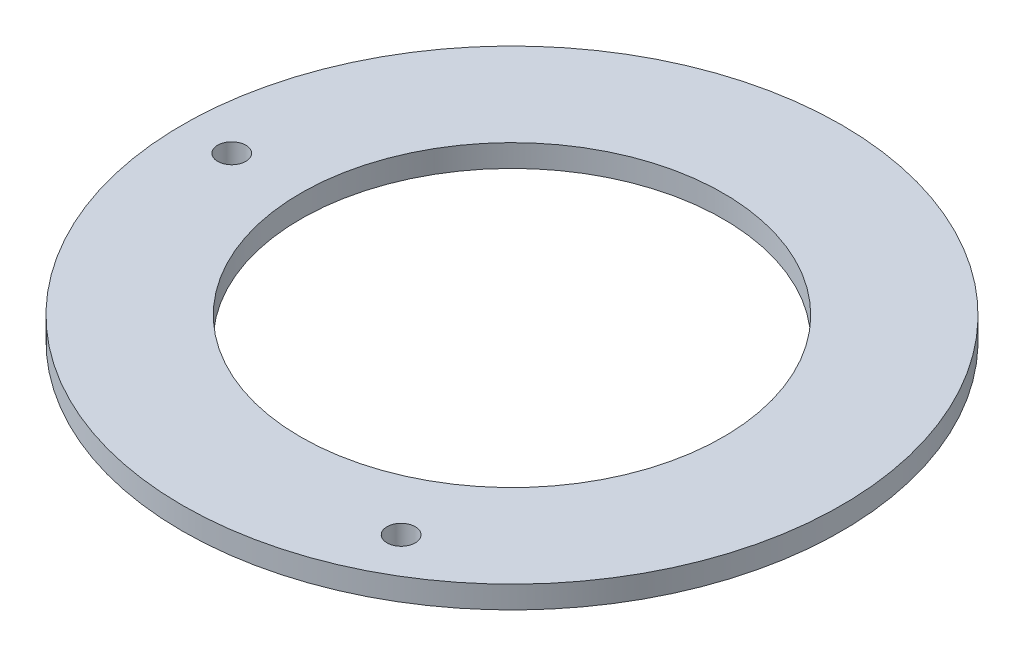
SolidWorks part; units mm, degrees
ref_plane "Front Plane" through (0, 0, 0) normal (0, 0, 1) x (1, 0, 0)
ref_plane "Top Plane" through (0, 0, 0) normal (0, 1, 0) x (1, 0, 0)
ref_plane "Right Plane" through (0, 0, 0) normal (1, 0, 0) x (0, 0, -1)
sketch "Sketch1" plane through (0, 0, 0) normal (0, 1, 0) x (1, 0, 0)
  line L0 (-39.8, 0) -> (0, 0) construction
  line L1 (-46.8, 0) -> (-39.8, 0) construction
  line L2 (0, 0) -> (22.5156, -41.0279) construction
  circle A0 centre (0, 0) radius 46.8
  circle A1 centre (0, 0) radius 30
  circle A2 centre (-39.8, 0) radius 2
  circle A3 centre (19.1479, -34.8912) radius 2
  point P6 (-46.8, 0)
  dimension "D1" = 93.6
  dimension "D2" = 60
  dimension "D4" = 4
  dimension "D5" = 4
  dimension "D3" = 7
  dimension "D6" = 7
  dimension "D7" = 68.5
extrude "Boss-Extrude1" add sketch "Sketch1" along normal blind 3.175
